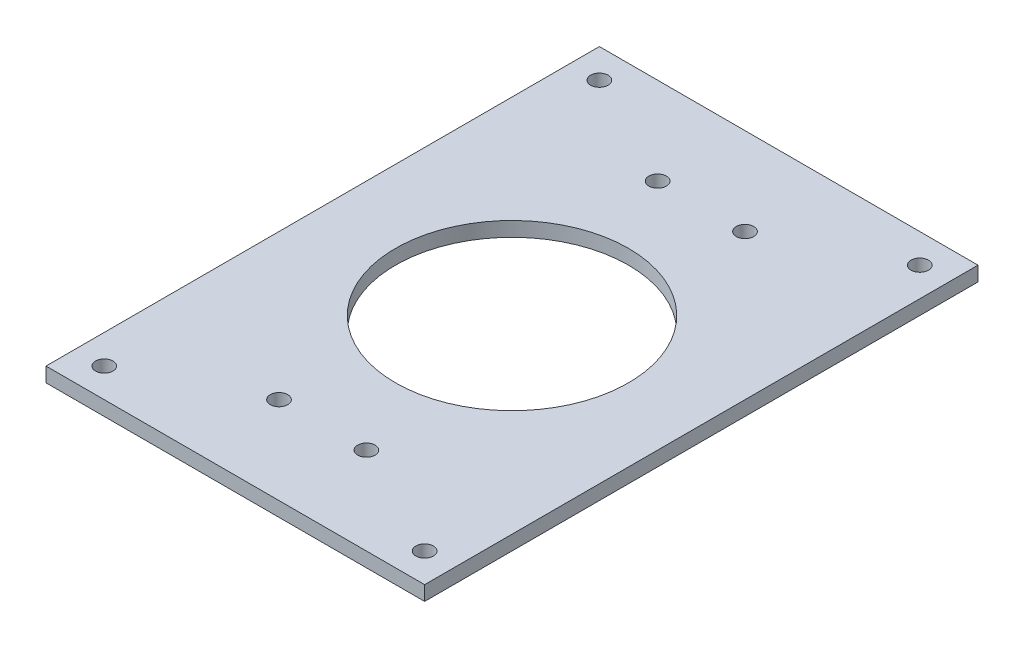
SolidWorks part; units mm, degrees
material "PET"
ref_plane "Alzado" through (0, 0, 0) normal (0, 0, 1) x (1, 0, 0)
ref_plane "Planta" through (0, 0, 0) normal (0, 1, 0) x (1, 0, 0)
ref_plane "Vista lateral" through (0, 0, 0) normal (1, 0, 0) x (0, 0, -1)
sketch "Croquis1" plane through (0, 0, 0) normal (0, 1, 0) x (1, 0, 0)
  line L1 (-32.5, -47.5) -> (32.5, -47.5)
  line L2 (-32.5, -47.5) -> (-32.5, 47.5)
  line L3 (-32.5, 47.5) -> (32.5, 47.5)
  line L4 (32.5, -47.5) -> (32.5, 47.5)
  line L5 (-32.5, -47.5) -> (32.5, 47.5) construction
  line L6 (-32.5, 47.5) -> (32.5, -47.5) construction
  point P0 (0, 0)
  dimension "D1" = 95
  dimension "D2" = 65
extrude "Saliente-Extruir1" add sketch "Croquis1" along normal blind 2.5
sketch "Croquis3" plane through (0, 2.5, 0) normal (0, 1, 0) x (1, 0, 0)
  line L0 (32.5, 47.5) -> (-32.5, 47.5) construction
  line L1 (32.5, -47.5) -> (32.5, 47.5) construction
  line L2 (-4.125, 0) -> (4.125, 0) construction
  line L3 (0, -4.125) -> (0, 4.125) construction
  circle A0 centre (27.5, 42.5) radius 1.5
  circle A1 centre (7.5, 32.5) radius 1.5
  circle A2 centre (7.5, -32.5) radius 1.5
  circle A3 centre (27.5, -42.5) radius 1.5
  circle A4 centre (-27.5, 42.5) radius 1.5
  circle A5 centre (-7.5, 32.5) radius 1.5
  circle A6 centre (-27.5, -42.5) radius 1.5
  circle A7 centre (-7.5, -32.5) radius 1.5
  dimension "D1" = 3
  dimension "D4" = 3
  dimension "D2" = 5
  dimension "D3" = 5
  dimension "D5" = 25
  dimension "D6" = 15
extrude "Cortar-Extruir2" cut sketch "Croquis3" against normal through all
sketch "Croquis4" plane through (0, 2.5, 0) normal (0, 1, 0) x (1, 0, 0)
  circle A0 centre (0, 0) radius 20
  dimension "D1" = 40
extrude "Cortar-Extruir3" cut sketch "Croquis4" against normal through all
